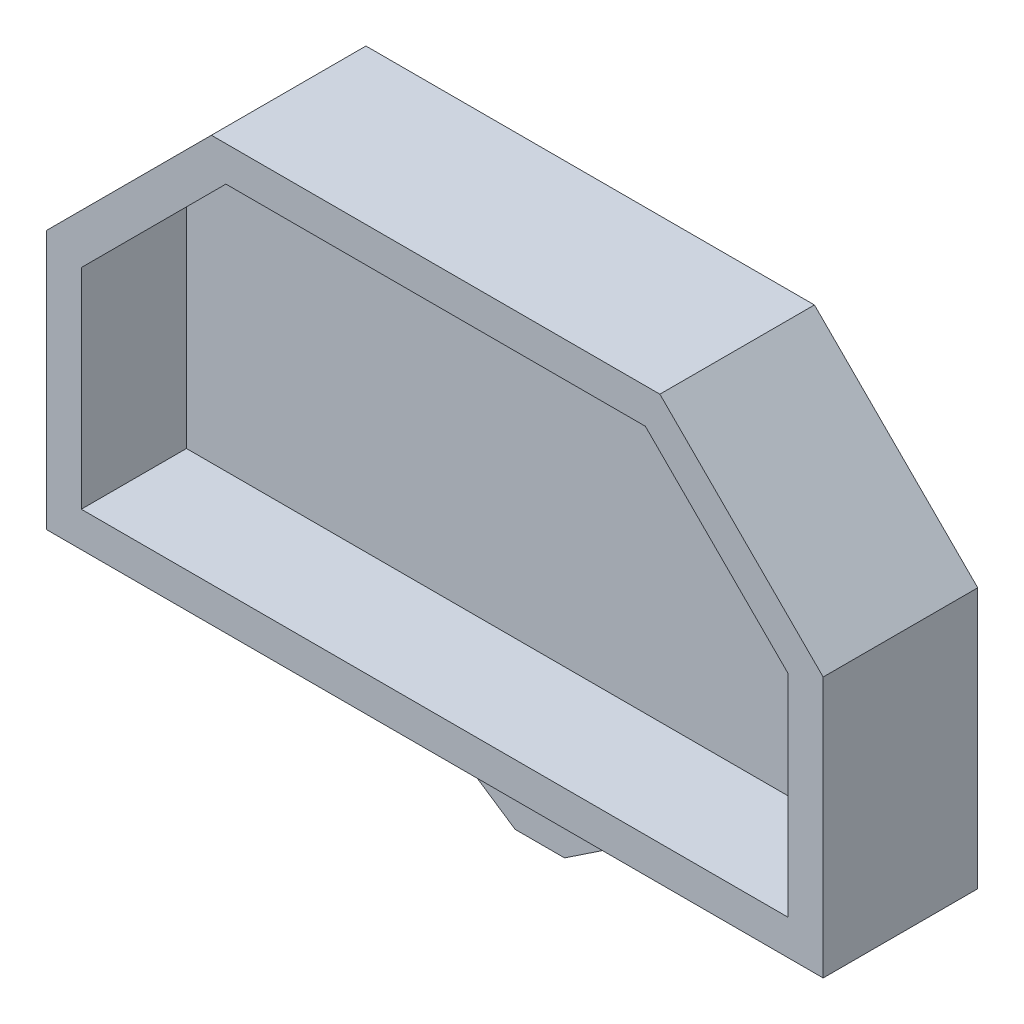
SolidWorks part; units mm, degrees
ref_plane "Front Plane" through (0, 0, 0) normal (0, 0, 1) x (1, 0, 0)
ref_plane "Top Plane" through (0, 0, 0) normal (0, 1, 0) x (1, 0, 0)
ref_plane "Right Plane" through (0, 0, 0) normal (1, 0, 0) x (0, 0, -1)
sketch "Sketch17" plane through (57.6167, 0, 0) normal (0, 0, -1) x (-1, 0, 0)
  line L0 (-6.8048, 0) -> (-6.8048, 15.2996)
  line L1 (-6.8048, 15.2996) -> (3.5421, 25.6465)
  line L2 (3.5421, 25.6465) -> (33.9435, 25.6465)
  line L3 (33.9435, 25.6465) -> (44.4222, 15.1678)
  line L4 (44.4222, 15.1678) -> (44.4222, 0)
  line L5 (44.4222, 0) -> (-6.8048, 0)
  line L6 (-9.3448, -2.54) -> (-9.3448, 16.3517)
  line L7 (-9.3448, 16.3517) -> (2.49, 28.1865)
  line L8 (2.49, 28.1865) -> (34.9956, 28.1865)
  line L9 (34.9956, 28.1865) -> (46.9622, 16.2199)
  line L10 (46.9622, 16.2199) -> (46.9622, -2.54)
  line L11 (46.9622, -2.54) -> (-9.3448, -2.54)
  dimension "D1" = 2.54
extrude "Boss-Extrude4" add sketch "Sketch17" along normal blind 7.62 separate body
sketch "Sketch20" plane through (0, 0, -7.62) normal (0, 0, -1) x (-1, 0, 0)
  line L0 (-66.9615, -2.54) -> (-66.9615, 16.3517)
  line L1 (-66.9615, 16.3517) -> (-55.1267, 28.1865)
  line L2 (-55.1267, 28.1865) -> (-22.6211, 28.1865)
  line L3 (-10.6545, 16.2199) -> (-22.6211, 28.1865) construction
  line L4 (-22.6211, 28.1865) -> (-10.6545, 16.2199)
  line L5 (-10.6545, 16.2199) -> (-10.6545, -2.54)
  line L6 (-10.6545, -2.54) -> (-10.6545, 16.2199) construction
  line L7 (-66.9615, -2.54) -> (-10.6545, -2.54) construction
  line L8 (-10.6545, -2.54) -> (-66.9615, -2.54)
extrude "Boss-Extrude5" add sketch "Sketch20" along normal blind 3.5814
sketch "Sketch21" plane through (0, 0, -11.2014) normal (0, 0, -1) x (-1, 0, 0)
  line L0 (-40.5987, -6.915) -> (-48.206, -6.915)
  line L1 (-40.5987, -2.54) -> (-40.5987, -6.915)
  line L2 (-37.0173, -2.54) -> (-37.0173, -6.915)
  line L3 (-48.206, -6.915) -> (-40.5987, -11.995)
  line L4 (-40.5987, -11.995) -> (-37.0173, -11.995)
  line L5 (-37.0173, -11.995) -> (-29.41, -6.915)
  line L6 (-29.41, -6.915) -> (-37.0173, -6.915)
  line L7 (-66.9615, -2.54) -> (-10.6545, -2.54) construction
  line L8 (-40.5987, -2.54) -> (-37.0173, -2.54)
  point P0 (-38.808, -4.7275)
  point P9 (-38.808, -2.54)
  point P10 (-38.808, -11.995)
  point P11 (-37.0173, -4.7275)
  point P12 (-38.808, -2.54)
  dimension "D1" = 3.5814
  dimension "D2" = 4.375
  dimension "D3" = 18.796
  dimension "D4" = 5.08
extrude "Boss-Extrude6" add sketch "Sketch21" against normal blind 3.5814
sketch "Sketch22" plane through (0, 0, -7.62) normal (0, 0, 1) x (1, 0, 0)
  line L0 (64.4215, 0) -> (13.1945, 0) construction
  line L1 (10.6545, -2.54) -> (10.6545, 16.2199) construction
  circle A0 centre (30.9745, 15.24) radius 2.6602
  dimension "D1" = 15.24
  dimension "D2" = 20.32
